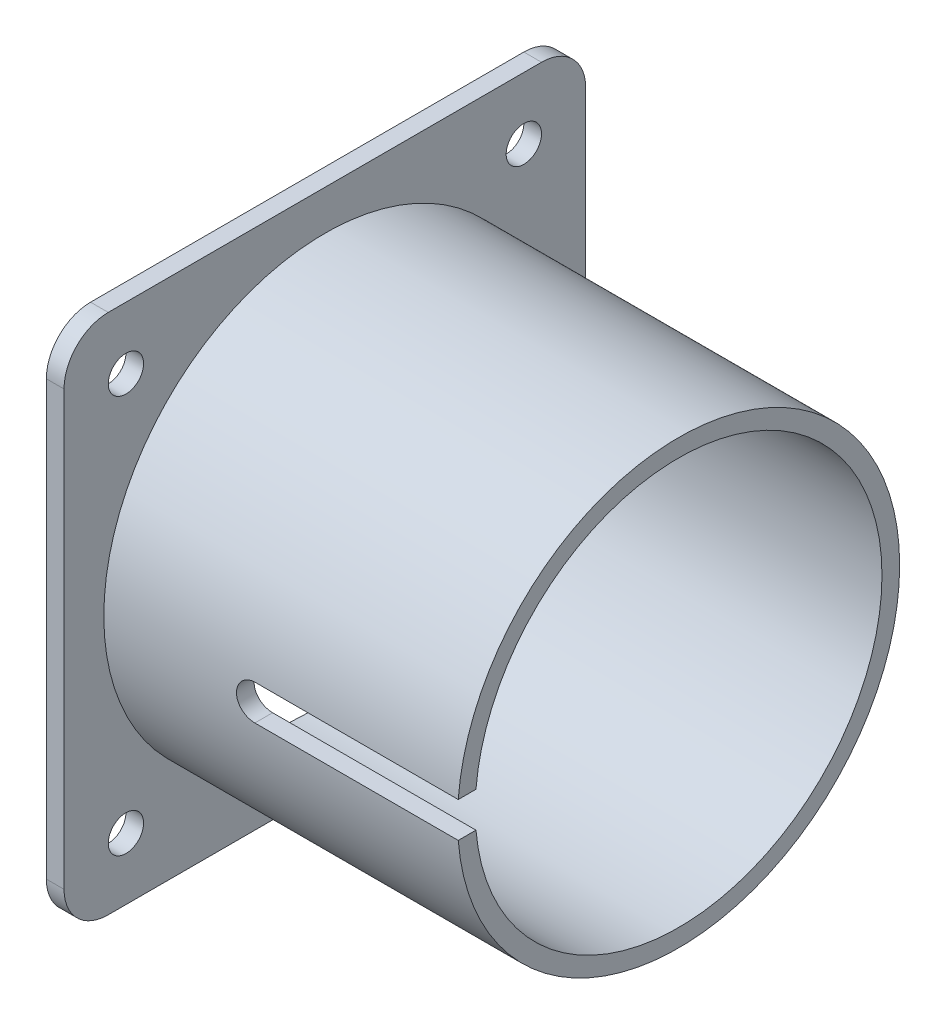
SolidWorks part; units mm, degrees
material "PVC Rígido"
ref_plane "Front" through (0, 0, 0) normal (0, 0, 1) x (1, 0, 0)
ref_plane "Top" through (0, 0, 0) normal (0, 1, 0) x (1, 0, 0)
ref_plane "Right" through (0, 0, 0) normal (1, 0, 0) x (0, 0, -1)
sketch "Croquis1" plane through (0, 0, 0) normal (1, 0, 0) x (0, 0, -1)
  line L0 (0, 0) -> (0, -46) construction
  line L1 (-49, 59) -> (49, 59)
  line L2 (-59, 49) -> (-59, -49)
  line L3 (-49, -59) -> (49, -59)
  line L4 (59, 49) -> (59, -49)
  line L5 (-59, 59) -> (59, -59) construction
  line L6 (-59, -59) -> (59, 59) construction
  line L7 (-45, 45) -> (45, 45)
  line L8 (-45, 45) -> (-45, -45)
  line L9 (-45, -45) -> (45, -45)
  line L10 (45, 45) -> (45, -45)
  line L11 (-45, 45) -> (45, -45) construction
  line L12 (-45, -45) -> (45, 45) construction
  line L13 (0, 0) -> (-45, 0) construction
  line L14 (-45, 45) -> (45, 45)
  circle A0 centre (0, 0) radius 46
  arc A1 (-59, 49) -> (-49, 59) centre (-49, 49) cw
  arc A2 (49, 59) -> (59, 49) centre (49, 49) cw
  arc A3 (59, -49) -> (49, -59) centre (49, -49) cw
  arc A4 (-49, -59) -> (-59, -49) centre (-49, -49) cw
  circle A5 centre (45, -45) radius 4
  circle A6 centre (-45, -45) radius 4
  circle A7 centre (-45, 45) radius 4
  circle A8 centre (45, 45) radius 4
  point P0 (0, 0)
  dimension "D2" = 92
  dimension "D3" = 10
  dimension "D4" = 10
  dimension "D6" = 8
  dimension "D1" = 118
  dimension "D5" = 90
extrude "Saliente-Extruir1" add sketch "Croquis1" along normal blind 4 contours A4 L3 A3 L4 A2 L1 A1 L2 L7 A8 L10 A0 A5 L9 A6 L8 A7 L14 | L8 A6 L9 A0 | A7 L8 A0 L14 | L10 A8 L7 A0 | A5 L10 A0 L9
sketch "Croquis2" plane through (4, 0, 0) normal (1, 0, 0) x (0, 0, -1)
  circle A0 centre (0, 0) radius 46
  circle A1 centre (0, 0) radius 50
  dimension "D1" = 100
extrude "Saliente-Extruir2" add sketch "Croquis2" along normal blind 80
ref_plane "Plano1" through (0, 0, 50) normal (0, 0, 1) x (1, 0, 0)
sketch "Croquis3" plane through (0, 0, 50) normal (0, 0, 1) x (1, 0, 0)
  line L0 (84, 0) -> (17.6913, 0) construction
  line L1 (84, -50) -> (84, 50) construction
  line L2 (84, 0) -> (84, 4)
  line L3 (84, 4) -> (38, 4)
  line L4 (84, -4) -> (38, -4)
  line L5 (84, -4) -> (84, 0)
  arc A0 (38, -4) -> (38, 4) centre (38, 0) cw
  dimension "D1" = 8
  dimension "D2" = 46
extrude "Cortar-Extruir1" cut sketch "Croquis3" against normal blind 10
sketch "Croquis4" plane through (0, 0, 0) normal (-1, 0, 0) x (0, 0, 1)
  circle A0 centre (0, 0) radius 50
  circle A1 centre (0, 0) radius 54
  dimension "D1" = 100
  dimension "D2" = 108
extrude "Cortar-Extruir2" cut sketch "Croquis4" against normal blind 3
